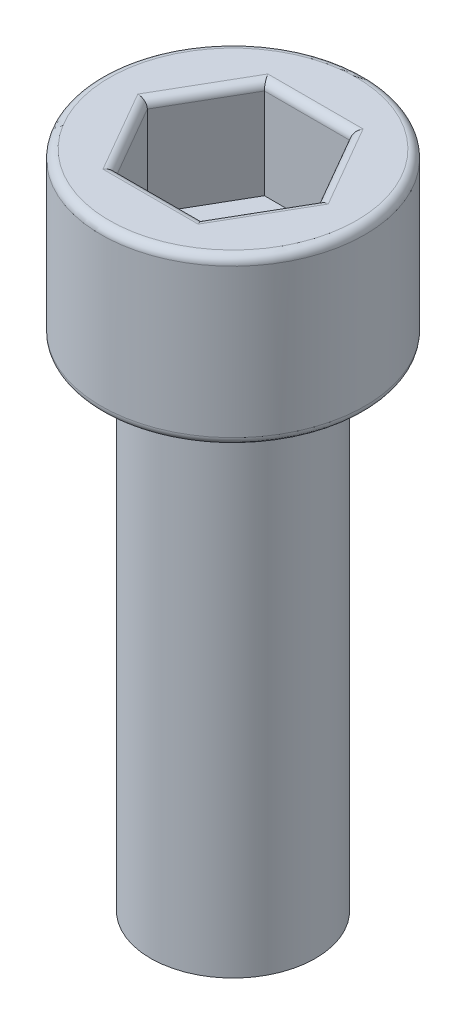
SolidWorks part; units mm, degrees
ref_plane "Front Plane" through (0, 0, 0) normal (0, 0, 1) x (1, 0, 0)
ref_plane "Top Plane" through (0, 0, 0) normal (0, 1, 0) x (1, 0, 0)
ref_plane "Right Plane" through (0, 0, 0) normal (1, 0, 0) x (0, 0, -1)
sketch "Sketch1" plane through (0, 0, 0) normal (0, 0, 1) x (1, 0, 0)
  line L0 (0, 21.3223) -> (0, -43.638) construction
sketch "Sketch2" plane through (0, 0, 0) normal (0, 0, 1) x (1, 0, 0)
  line L0 (0, 5) -> (4, 5)
  line L1 (0, 200021.3223) -> (0, -200043.638) construction
  line L2 (4, 5) -> (4, 0)
  line L3 (4, 0) -> (2.5, 0)
  line L4 (2.5, 0) -> (2.5, -15)
  line L5 (2.5, -15) -> (0, -15)
  line L6 (0, -15) -> (0, 5)
  dimension "D1" = 2.5
  dimension "D2" = 4
  dimension "D3" = 5
  dimension "D4" = 15
revolve "Revolve1" add sketch "Sketch2" angle 360 about L0
sketch "Sketch3" plane through (0, 5, 0) normal (0, 1, 0) x (1, 0, 0)
  line L0 (0, 0) -> (2.5981, 0) construction
  line L1 (2.5981, 0) -> (1.299, 2.25)
  line L2 (1.299, 2.25) -> (-1.299, 2.25)
  line L3 (-1.299, 2.25) -> (-2.5981, 0)
  line L4 (-2.5981, 0) -> (-1.299, -2.25)
  line L5 (-1.299, -2.25) -> (1.299, -2.25)
  line L6 (1.299, -2.25) -> (2.5981, 0)
  circle A0 centre (0, 0) radius 2.25 construction
  dimension "D1" = 4.5
extrude "Cut-Extrude1" cut sketch "Sketch3" against normal blind 3
fillet "Fillet1" radius 0.25 9 edges at (-2.5, 0, 0) (-4, 0, 0) (-4, 5, 0) (0, 5, -2.25) (-1.9486, 5, -1.125) (-1.9486, 5, 1.125) (0, 5, 2.25) (1.9486, 5, 1.125) (1.9486, 5, -1.125)
